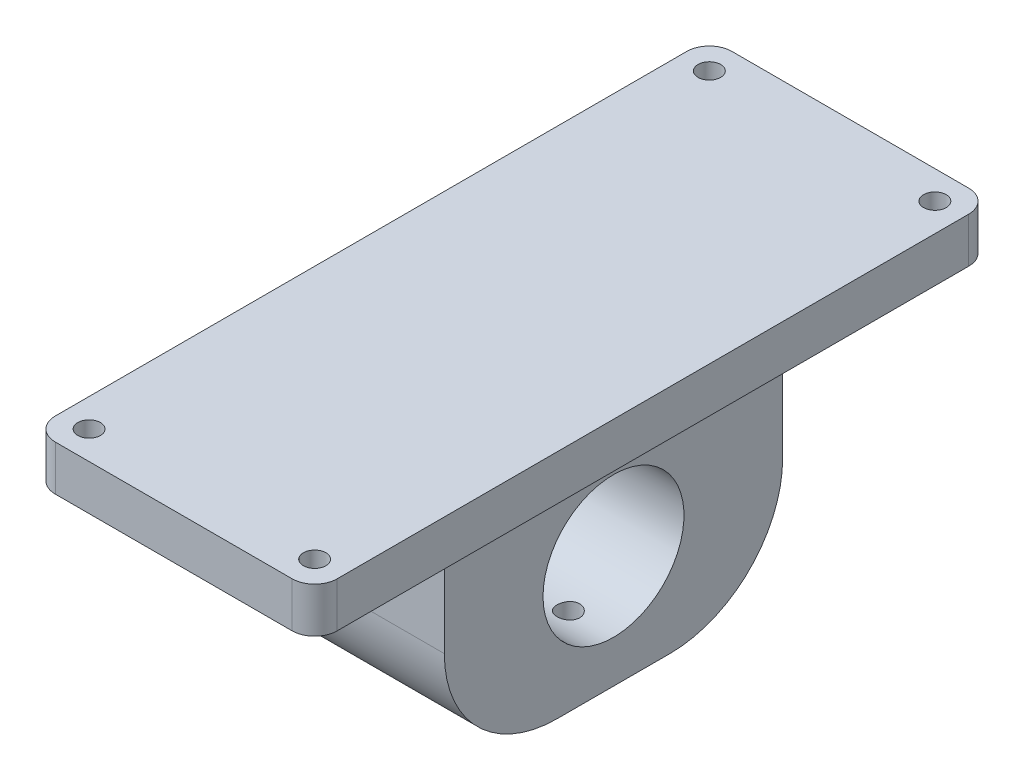
SolidWorks part; units mm, degrees
material "ABS"
ref_plane "Alzado" through (0, 0, 0) normal (0, 0, 1) x (1, 0, 0)
ref_plane "Planta" through (0, 0, 0) normal (0, 1, 0) x (1, 0, 0)
ref_plane "Vista lateral" through (0, 0, 0) normal (1, 0, 0) x (0, 0, -1)
sketch "Sketch1" plane through (0, 0, 0) normal (0, 1, 0) x (1, 0, 0)
  line L1 (-135, 60) -> (-85, 60)
  line L2 (-135, 60) -> (-135, -60)
  line L3 (-135, -60) -> (-85, -60)
  line L4 (-85, 60) -> (-85, -60)
  line L5 (-135, 60) -> (-85, -60) construction
  line L6 (-135, -60) -> (-85, 60) construction
  point P0 (-110, 0)
  dimension "D1" = 50
  dimension "D2" = 120
  dimension "D3" = 110
extrude "Boss-Extrude1" add sketch "Sketch1" along normal blind 8
sketch "Sketch2" plane through (0, 8, 0) normal (0, 1, 0) x (1, 0, 0)
  line L0 (-135, 60) -> (-135, -60) construction
  line L1 (-85, 60) -> (-135, 60) construction
  circle A0 centre (-130, 55) radius 2
  dimension "D1" = 4
  dimension "D2" = 5
  dimension "D3" = 5
extrude "Cut-Extrude1" cut sketch "Sketch2" against normal blind 10
pattern_linear "LPattern1" count 2 spacing 40 along (1, 0, 0) of "Cut-Extrude1"
pattern_linear "LPattern2" count 2 spacing 110 along (0, 0, 1) of "LPattern1", "Cut-Extrude1"
sketch "Sketch5" plane through (0, 0, 0) normal (0, -1, 0) x (1, 0, 0)
  line L0 (-110, 30) -> (-110, -30) construction
  line L1 (-92, 30) -> (-92, -30)
  line L2 (-128, 30) -> (-128, -30)
  line L3 (-85, -60) -> (-135, -60) construction
  line L4 (-85, 60) -> (-85, -60) construction
  line L5 (-135, -60) -> (-135, 60) construction
  arc A0 (-92, 30) -> (-128, 30) centre (-110, 30) ccw
  arc A1 (-128, -30) -> (-92, -30) centre (-110, -30) ccw
  point P2 (-110, 0)
  point P17 (-85, 0)
  dimension "D2" = 18
  dimension "D1" = 60
  dimension "D3" = 25
extrude "Boss-Extrude2" add sketch "Sketch5" along normal blind 40
sketch "Sketch6" plane through (-128, 0, 0) normal (-1, 0, 0) x (0, 0, 1)
  line L0 (-30, -40) -> (-30, 0) construction
  circle A0 centre (0, -20) radius 12.5
  point P6 (-30, -20)
  dimension "D1" = 25
extrude "Cut-Extrude2" cut sketch "Sketch6" against normal through all
sketch "Sketch7" plane through (-92, 0, 0) normal (1, 0, 0) x (0, 0, -1)
  line L0 (-30, 0) -> (-30, -20)
  line L1 (-10, -40) -> (10, -40)
  line L2 (30, -20) -> (30, 0)
  line L3 (-30, 0) -> (-48, 0)
  line L4 (-48, 0) -> (-48, -40)
  line L5 (-48, -40) -> (-10, -40)
  line L6 (30, 0) -> (48, 0)
  line L7 (48, 0) -> (48, -40)
  line L8 (48, -40) -> (10, -40)
  arc A0 (10, -40) -> (30, -20) centre (10, -20) ccw
  arc A1 (-30, -20) -> (-10, -40) centre (-10, -20) ccw
  point P10 (30, -40)
  point P13 (-30, -40)
  line M3 (-30, 0) -> (-30, -40)
  line M4 (-30, -40) -> (30, -40)
  line M5 (30, -40) -> (30, 0)
  dimension "D1" = 20
extrude "Cut-Extrude3" cut sketch "Sketch7" against normal through all contours L4 L5 L3 M3 | A1 M3 M4 | A0 M4 M5 | L8 L7 L6 M5
fillet "Fillet1" radius 4 4 edges at (-135, 4, -60) (-85, 4, -60) (-85, 4, 60) (-135, 4, 60)
sketch "Sketch8" plane through (0, -40, 0) normal (0, -1, 0) x (1, 0, 0)
  line L0 (-128, 10) -> (-92, 10) construction
  line L1 (-128, 10) -> (-128, -10) construction
  circle A1 centre (-110, 0) radius 2
  point P4 (-110, 10)
  point P7 (-128, 0)
  dimension "D1" = 4
extrude "Cut-Extrude4" cut sketch "Sketch8" against normal blind 10
sketch "Sketch9" plane through (0, -40, 0) normal (0, -1, 0) x (1, 0, 0)
  circle A0 centre (-110, 0) radius 2.5
  dimension "D1" = 5
extrude "Cut-Extrude5" cut sketch "Sketch9" against normal blind 1
pattern_linear "LPattern3" count 2 spacing 10 along (1, 0, 0) count 2 spacing 10 along (-1, 0, 0) of "Cut-Extrude4", "Cut-Extrude5"
